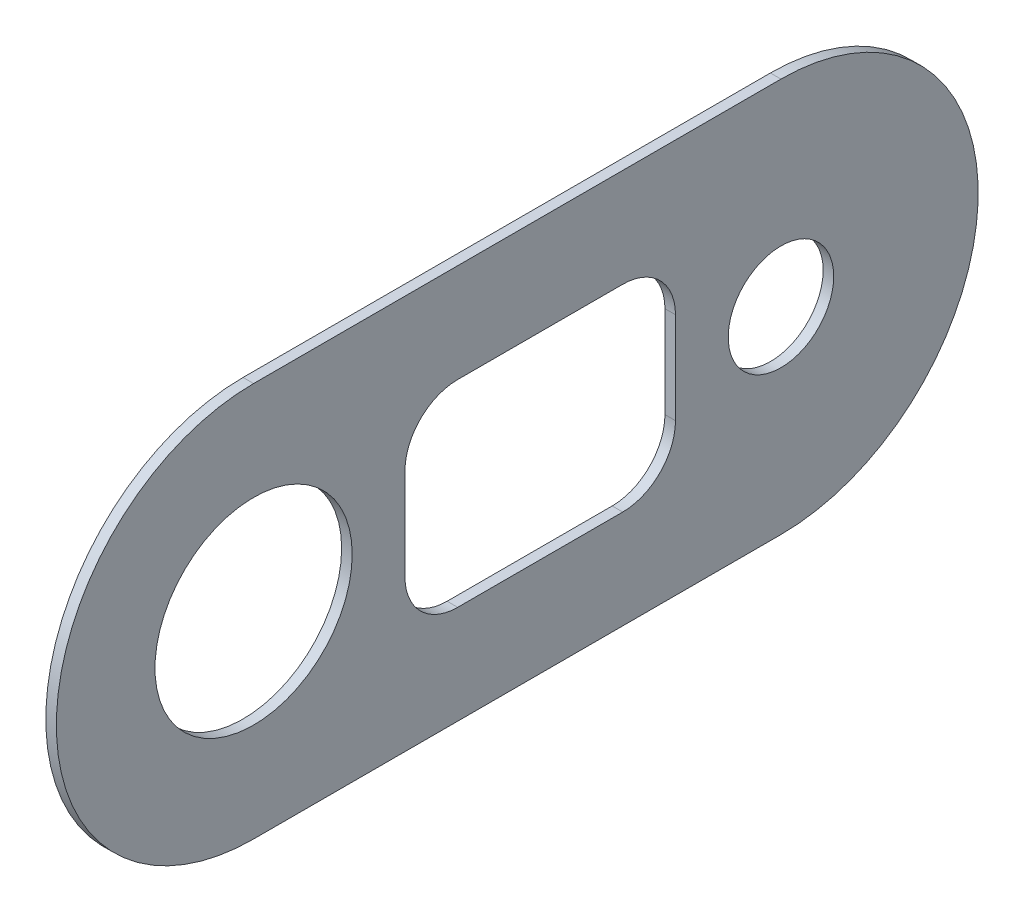
SolidWorks part; units mm, degrees
material "6061-T6 (SS)"
ref_plane "Front Plane" through (0, 0, 0) normal (1, 0, 0) x (0, 1, 0)
ref_plane "Top Plane" through (0, 0, 0) normal (0, 0, 1) x (0, 1, 0)
ref_plane "Right Plane" through (0, 0, 0) normal (0, 1, 0) x (-1, 0, 0)
sketch "Sketch1" plane through (0, 0, 0) normal (1, 0, 0) x (0, 1, 0)
  line L0 (0, 0) -> (0, 127)
  line L1 (94.996, 0) -> (94.996, 127)
  line L6 (36.449, 90.551) -> (58.547, 90.551)
  line L7 (71.247, 77.851) -> (71.247, 38.1)
  line L8 (58.547, 25.4) -> (36.449, 25.4)
  line L9 (23.749, 38.1) -> (23.749, 77.851)
  arc A0 (0, 127) -> (94.996, 127) centre (47.498, 127) cw
  arc A1 (0, 0) -> (94.996, 0) centre (47.498, 0) ccw
  circle A2 centre (47.498, 0) radius 12.7
  circle A3 centre (47.498, 127) radius 23.749
  arc A8 (58.547, 90.551) -> (71.247, 77.851) centre (58.547, 77.851) cw
  arc A9 (36.449, 90.551) -> (23.749, 77.851) centre (36.449, 77.851) ccw
  arc A10 (36.449, 25.4) -> (23.749, 38.1) centre (36.449, 38.1) cw
  arc A11 (71.247, 38.1) -> (58.547, 25.4) centre (58.547, 38.1) cw
  dimension "D1" = 25.4
  dimension "D2" = 47.498
  dimension "D4" = 47.498
  dimension "D7" = 12.7
  dimension "D3" = 127
  dimension "D5" = 36.449
  dimension "D6" = 25.4
extrude "Boss-Extrude2" add sketch "Sketch1" along normal blind 2.54
equation "\"deflmax\"= .005"
equation "\"modulus\"= 10000000"
equation "\"Smax\"= 40000"
equation "\"force\"= 800"
equation "\"l1\"= 1"
equation "\"SF\"= 4"
equation "\"d\" = \"SF\" * ( ( \"force\" * \"l1\" * 16 ) / ( \"Smax\" * pi ) ) ^ ( 1 / 3 )"
equation "\"t2\"= \"force\" / ( \"d\" * \"Smax\" )"
equation "\"l2\"= \"modulus\" * \"d\" * \"t2\" * \"deflmax\" / \"force\""
equation "\"t4\" = .5"
equation "\"l4\"= 1.499"
equation "\"w4\" = \"l4\" * \"force\" * \"SF\" / 2 / ( \"modulus\" * \"deflmax\" * \"t4\" )"
equation "\"l5\"= \"w4\" + .9992"
equation "\"w5\" = ( ( \"force\" * \"w4\" ^ 3 * 3 ) / ( \"modulus\" * \"t4\" * \"deflmax\" * 4 ) ) ^ ( 1 / 3 )"
equation "\"l3\"= .498 + 2 * .9992 + ( \"w4\" * 2 )"
equation "\"w3\"= ( ( \"force\" * \"l3\" ^ 3 ) / ( \"modulus\" * \"t4\" * \"deflmax\" * 4 ) ) ^ ( 1 / 3 )"
equation "\"a\"= .498"
equation "\"b\"= .9992"
equation "\"l6\"= \"A6\" * \"modulus\" * \"deflmax\" / \"force\""
equation "\"t6\"= \"A6\" / ( 2 * \"R\" - \"d\" )"
equation "\"A6\"= \"SF\" * \"force\" / \"Smax\""
equation "\"R\"= \"d\""
